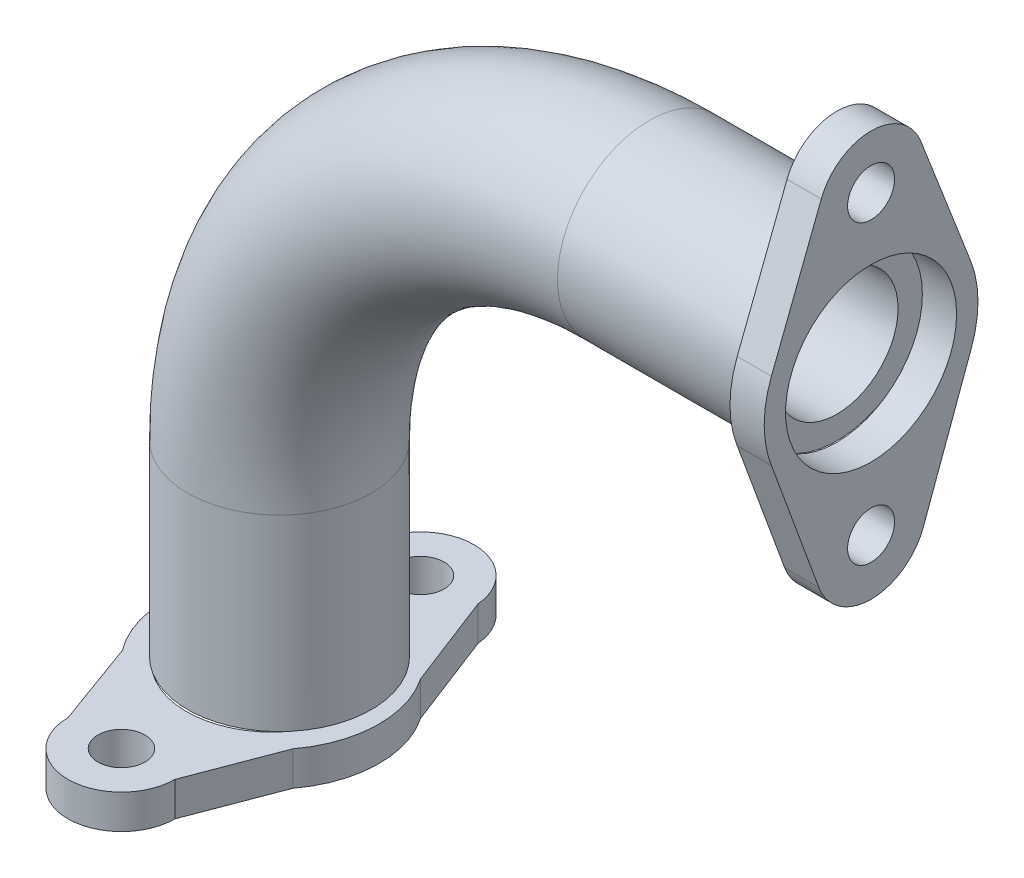
SolidWorks part; units mm, degrees
ref_plane "Front Plane" through (0, 0, 0) normal (0, 0, 1) x (1, 0, 0)
ref_plane "Top Plane" through (0, 0, 0) normal (0, 1, 0) x (1, 0, 0)
ref_plane "Right Plane" through (0, 0, 0) normal (1, 0, 0) x (0, 0, -1)
sketch "Sketch1" plane through (0, 0, 0) normal (0, 0, 1) x (1, 0, 0)
  line L0 (-59.0087, 84.3401) -> (-15.1734, 84.3401)
  line L1 (-145.5087, -2.1599) -> (-145.5087, -45.9951)
  arc A0 (-59.0087, 84.3401) -> (-145.5087, -2.1599) centre (-59.0087, -2.1599) ccw
  point P4 (-145.5087, 20.0049)
  point P6 (0, 0)
  point P7 (-120.1734, 59.0049)
  dimension "D1" = 86.5
  dimension "D4" = 223.5444
  dimension "D2" = 105
  dimension "D3" = 105
sweep "Sweep1" add path "Sketch1" circular profile diameter 43 parameters "D3"=43
sketch "Sketch8" plane through (-15.1734, 0, 0) normal (1, 0, 0) x (0, 0, -1)
  line L0 (0, 129.6274) -> (0, 35.4849) construction
  line L1 (-24.9977, 82.2192) -> (24.9977, 82.2192) construction
  line L4 (11.6543, 121.647) -> (23.3086, 91.5955)
  line L5 (23.3086, 73.5168) -> (12.2013, 43.2393)
  line L6 (-23.3086, 73.5168) -> (-12.2013, 43.2393)
  line L7 (-11.6543, 121.647) -> (-23.3086, 91.5955)
  arc A1 (11.6543, 121.647) -> (-11.6543, 121.647) centre (0, 117.1274) ccw
  arc A3 (23.3086, 73.5168) -> (23.3086, 91.5955) centre (0, 82.5562) ccw
  arc A5 (-23.3086, 91.5955) -> (-23.3086, 73.5168) centre (0, 82.5562) ccw
  arc A6 (-12.2013, 43.2393) -> (12.2013, 43.2393) centre (0, 47.7643) ccw
  point P3 (-22.7617, 91.5417)
  point P5 (0, 0)
  point P8 (0, 82.5562)
  point P10 (-25, 82.5562)
  point P15 (0, 0)
  dimension "D1" = 94.1424
  dimension "D2" = 25
  dimension "D3" = 25
  dimension "D4" = 25
  dimension "D5" = 25
  dimension "D6" = 30.0516
extrude "Boss-Extrude1" add sketch "Sketch8" along normal blind 8
sketch "Sketch9" plane through (0, -45.9951, 0) normal (0, -1, 0) x (1, 0, 0)
  line L4 (-157.8618, 37.1031) -> (-165.1358, 17.1031)
  line L5 (-132.8618, 37.1031) -> (-125.2525, 17.1031)
  line L6 (-132.9729, -33.8998) -> (-124.5156, -12.0243)
  line L7 (-157.8802, -34.041) -> (-164.3479, -14.041)
  arc A0 (-124.5156, -12.0243) -> (-125.2525, 17.1031) centre (-145.1941, 2.0256) ccw
  arc A1 (-132.8618, 37.1031) -> (-157.8618, 37.1031) centre (-145.3618, 37.1031) ccw
  arc A2 (-157.8802, -34.041) -> (-132.9729, -33.8998) centre (-145.4326, -32.8971) ccw
  arc A3 (-165.1358, 17.1031) -> (-164.3479, -14.041) centre (-145.1941, 2.0256) ccw
  point P0 (-164.3479, 17.1031)
  point P1 (-145.3618, 49.6031)
  point P2 (-145.3618, -45.3969)
  point P3 (-170.1861, 1.3933)
  point P7 (-126.1713, 15.845)
  point P12 (-120.2021, 2.6578)
  point P17 (0, 0)
  point P19 (0, 0)
  point P20 (-120.917, 4.5)
  point P21 (0, 0)
  point P22 (0, 0)
  dimension "D1" = 25
  dimension "D2" = 25
  dimension "D3" = 50
  dimension "D4" = 95
  dimension "D5" = 50
  dimension "D6" = 20
  dimension "D7" = 20
  dimension "D8" = 20
  dimension "D9" = 21.8755
extrude "Boss-Extrude2" add sketch "Sketch9" along normal blind 8
sketch "Sketch10" plane through (-7.1734, 0, 0) normal (1, 0, 0) x (0, 0, -1)
  circle A0 centre (0, 82.5562) radius 20
  dimension "D1" = 40
extrude "Cut-Extrude1" cut sketch "Sketch10" against normal blind 8
sketch "Sketch12" plane through (0, -53.9951, 0) normal (0, -1, 0) x (1, 0, 0)
  circle A0 centre (-145.1941, 2.0256) radius 20
  dimension "D1" = 40
extrude "Cut-Extrude2" cut sketch "Sketch12" against normal blind 8
sketch "Sketch13" plane through (0, -45.9951, 0) normal (0, -1, 0) x (1, 0, 0)
  circle A0 centre (-145.3618, 37.1031) radius 10
  circle A1 centre (-145.3618, 37.1031) radius 5.5
  circle A2 centre (-145.4326, -32.8971) radius 10
  circle A3 centre (-145.4326, -32.8971) radius 5.5
  dimension "D1" = 20
  dimension "D2" = 11
  dimension "D3" = 20
  dimension "D4" = 11
extrude "Cut-Extrude3" cut sketch "Sketch13" along normal blind 22 contours A1 | A3
sketch "Sketch14" plane through (-7.1734, 0, 0) normal (1, 0, 0) x (0, 0, -1)
  circle A0 centre (0, 117.1274) radius 5.5
  circle A1 centre (0, 47.7643) radius 5.5
  circle A2 centre (0, 117.1274) radius 10
  circle A3 centre (0, 47.7643) radius 10
  dimension "D1" = 20
  dimension "D2" = 20
  dimension "D3" = 11
  dimension "D4" = 11
extrude "Cut-Extrude4" cut sketch "Sketch14" against normal blind 22 contours A0 | A1
sketch "Sketch26" plane through (-15.1734, 0, 0) normal (1, 0, 0) x (0, 0, -1)
  circle A1 centre (0, 82.5562) radius 14.3086
extrude "Cut-Extrude6" cut sketch "Sketch26" against normal blind 75
sketch "Sketch27" plane through (0, -45.9951, 0) normal (0, -1, 0) x (1, 0, 0)
  circle A0 centre (-145.5087, 0) radius 17.5
  dimension "D1" = 35
extrude "Cut-Extrude8" cut sketch "Sketch27" against normal blind 46
